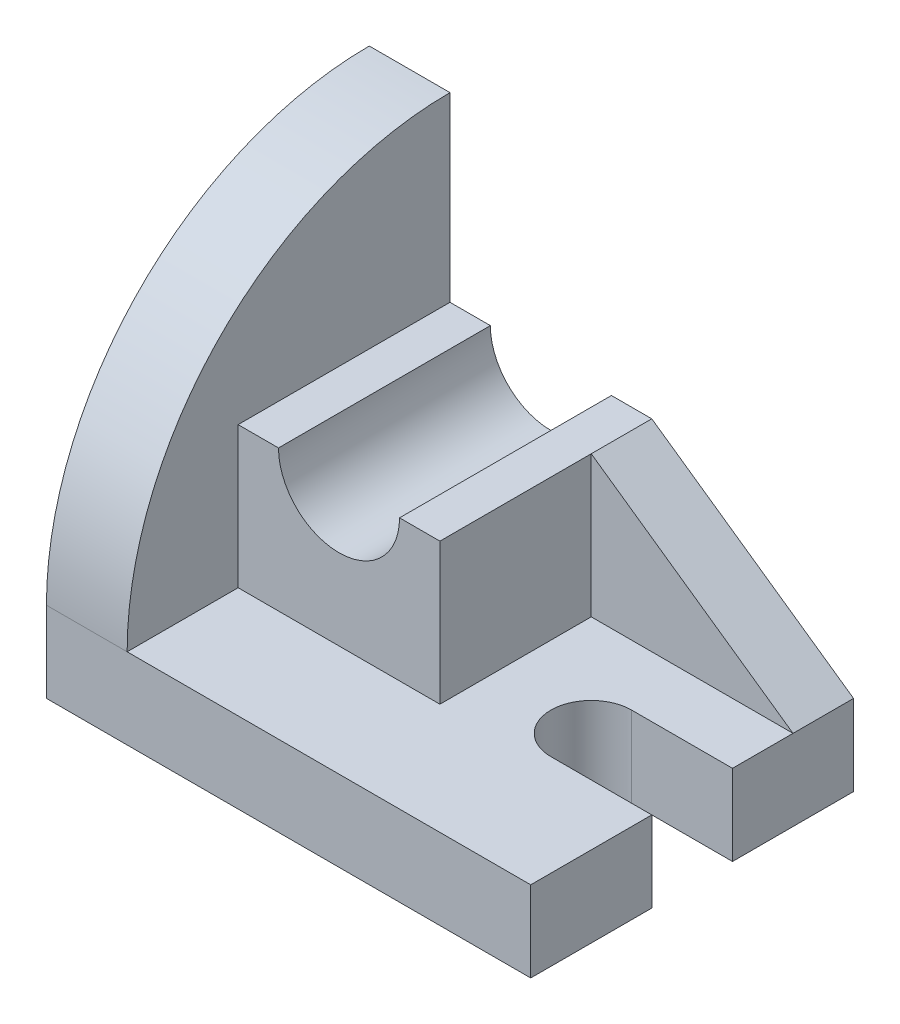
SolidWorks part; units mm, degrees
ref_plane "Front Plane" through (0, 0, 0) normal (0, 0, 1) x (1, 0, 0)
ref_plane "Top Plane" through (0, 0, 0) normal (0, 1, 0) x (1, 0, 0)
ref_plane "Right Plane" through (0, 0, 0) normal (1, 0, 0) x (0, 0, -1)
sketch "Sketch1" plane through (0, 0, 0) normal (0, 1, 0) x (1, 0, 0)
  line L1 (-121.92, -81.28) -> (121.92, -81.28)
  line L2 (-121.92, -81.28) -> (-121.92, 81.28)
  line L3 (-121.92, 81.28) -> (121.92, 81.28)
  line L4 (121.92, -81.28) -> (121.92, -20.32)
  line L7 (121.92, 20.32) -> (71.12, 20.32)
  line L10 (121.92, -20.32) -> (71.12, -20.32)
  line L11 (121.92, 20.32) -> (121.92, 81.28)
  arc A0 (71.12, 20.32) -> (71.12, -20.32) centre (71.12, 0) ccw
  point P0 (0, 0)
  dimension "D1" = 162.56
  dimension "D2" = 243.84
  dimension "D4" = 50.8
extrude "Boss-Extrude1" add sketch "Sketch1" along normal blind 40.64
sketch "Sketch2" plane through (-121.92, 0, 0) normal (-1, 0, 0) x (0, 0, 1)
  line L4 (-81.28, 40.64) -> (-81.28, 203.2)
  line L9 (-81.28, 0) -> (81.28, 0)
  line L10 (81.28, 0) -> (81.28, 40.64)
  line L11 (81.28, 40.64) -> (-81.28, 40.64)
  line L12 (-81.28, 40.64) -> (-81.28, 0)
  line L15 (81.28, 40.64) -> (-81.28, 40.64)
  arc A1 (81.28, 40.64) -> (-81.28, 203.2) centre (-81.28, 40.64) ccw
  dimension "D1" = 162.56
  dimension "D2" = 0
extrude "Boss-Extrude2" add sketch "Sketch2" against normal blind 40.64
sketch "Sketch3" plane through (0, 40.64, 0) normal (0, 1, 0) x (1, 0, 0)
  line L0 (-81.28, 81.28) -> (20.32, 81.28)
  line L1 (121.92, 81.28) -> (-81.28, 81.28) construction
  line L2 (20.32, 81.28) -> (20.32, -25.4)
  line L3 (20.32, -25.4) -> (-81.28, -25.4)
  line L4 (-81.28, -81.28) -> (-81.28, 81.28) construction
  line L5 (-81.28, -25.4) -> (-81.28, 81.28)
  dimension "D1" = 101.6
  dimension "D2" = 106.68
extrude "Boss-Extrude3" add sketch "Sketch3" along normal blind 71.12
sketch "Sketch4" plane through (0, 0, 25.4) normal (0, 0, 1) x (1, 0, 0)
  line L0 (-81.28, 111.76) -> (20.32, 111.76) construction
  line L1 (-60.96, 111.76) -> (0, 111.76)
  arc A0 (0, 111.76) -> (-60.96, 111.76) centre (-30.48, 111.76) cw
extrude "Cut-Extrude1" cut sketch "Sketch4" against normal through all and the other way through all
sketch "Sketch5" plane through (0, 40.64, 0) normal (0, 1, 0) x (1, 0, 0)
  line L0 (121.92, 20.32) -> (121.92, 81.28) construction
  line L1 (20.32, 81.28) -> (121.92, 81.28)
  line L2 (20.32, 81.28) -> (20.32, 50.8)
  line L3 (20.32, 50.8) -> (121.92, 50.8)
  line L4 (121.92, 81.28) -> (121.92, 50.8)
  dimension "D1" = 101.6
  dimension "D2" = 30.48
extrude "Boss-Extrude4" add sketch "Sketch5" along normal blind 71.12
sketch "Sketch6" plane through (0, 0, -50.8) normal (0, 0, 1) x (1, 0, 0)
  line L0 (20.32, 111.76) -> (121.92, 40.64)
  line L1 (121.92, 40.64) -> (121.92, 111.76)
  line L2 (121.92, 111.76) -> (20.32, 111.76)
extrude "Cut-Extrude2" cut sketch "Sketch6" against normal blind 71.12
